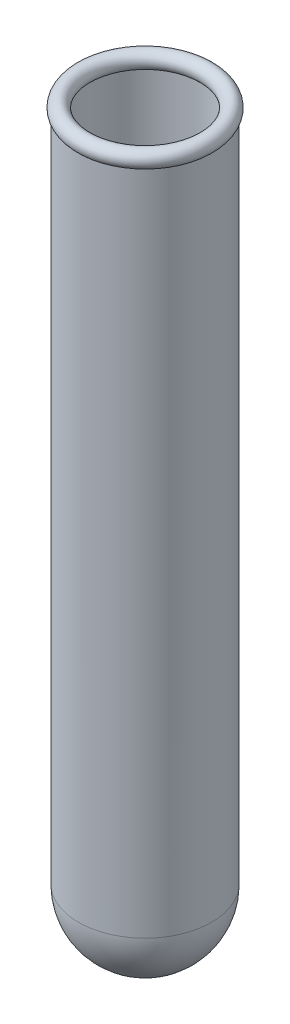
SolidWorks part; units mm, degrees
ref_plane "Front Plane" through (0, 0, 0) normal (0, 0, 1) x (1, 0, 0)
ref_plane "Top Plane" through (0, 0, 0) normal (0, 1, 0) x (1, 0, 0)
ref_plane "Right Plane" through (0, 0, 0) normal (1, 0, 0) x (0, 0, -1)
sketch "Sketch1" plane through (0, 0, 0) normal (0, 0, 1) x (1, 0, 0)
  line L0 (6, 0) -> (6, 60)
  line L2 (-5, 0) -> (-5, 60)
  line L3 (-5, 60) -> (5, 60)
  line L4 (5, 0) -> (5, 60)
  line L5 (-6, 61) -> (4.8933, 61)
  line L6 (-6, 0) -> (-6, 61)
  line L7 (0, 0) -> (0, 60) construction
  line L8 (-6, 61) -> (6, 61) construction
  line L9 (6, 0) -> (6, 61) construction
  line L10 (0, -5) -> (0, -6)
  arc A0 (-5, 0) -> (5, 0) centre (0, 0) ccw
  arc A1 (-6, 0) -> (6, 0) centre (0, 0) ccw
  arc A5 (6, 60) -> (5, 60) centre (5.5, 60.559) ccw
  point P13 (5.5, 59.9258)
  dimension "D1" = 10
  dimension "D4" = 1.5
  dimension "D2" = 60
  dimension "D3" = 1
revolve "Revolve1" add sketch "Sketch1" angle 360 about L7
